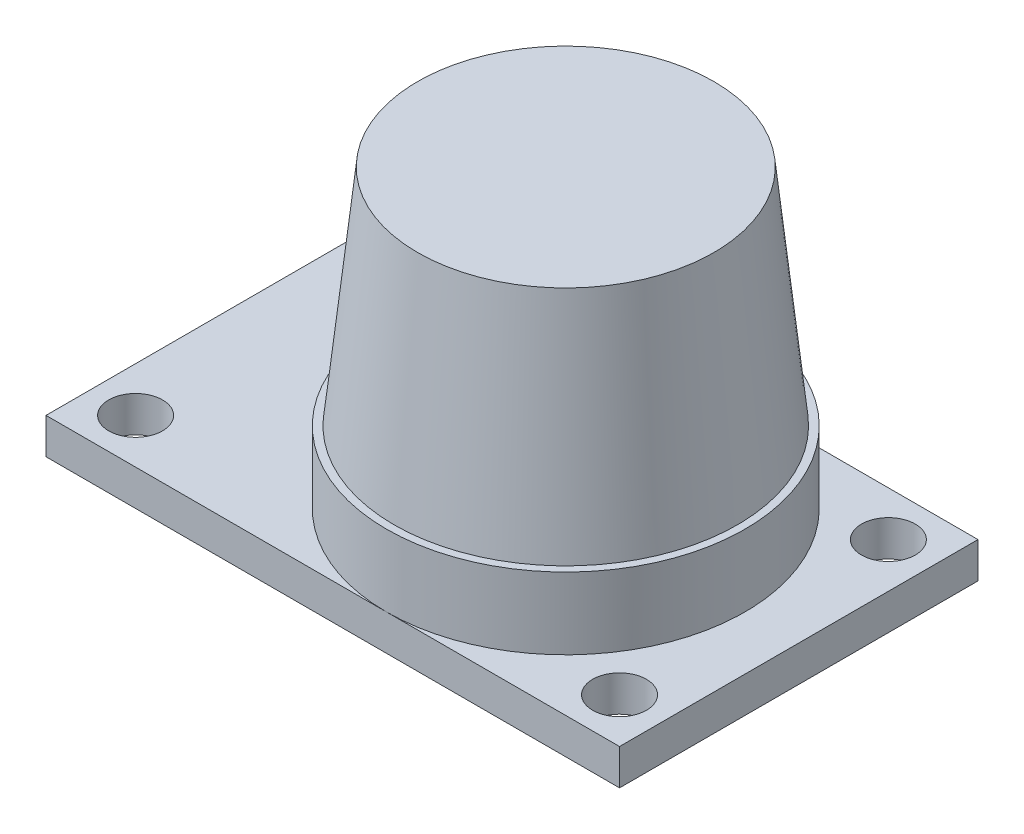
SolidWorks part; units mm, degrees
ref_plane "Alzado" through (0, 0, 0) normal (0, 0, 1) x (1, 0, 0)
ref_plane "Planta" through (0, 0, 0) normal (0, 1, 0) x (1, 0, 0)
ref_plane "Vista lateral" through (0, 0, 0) normal (1, 0, 0) x (0, 0, -1)
sketch "Croquis1" plane through (0, 0, 0) normal (0, 1, 0) x (1, 0, 0)
  line L0 (-13.5, 7.5) -> (-13.5, -7.5) construction
  line L1 (-16, -10) -> (16, -10)
  line L2 (-16, -10) -> (-16, 10)
  line L3 (-16, 10) -> (16, 10)
  line L4 (16, -10) -> (16, 10)
  line L5 (-16, -10) -> (16, 10) construction
  line L6 (-16, 10) -> (16, -10) construction
  line L7 (-13.5, 7.5) -> (13.5, 7.5) construction
  circle A0 centre (-13.5, 7.5) radius 1.5
  circle A1 centre (13.5, 7.5) radius 1.5
  circle A2 centre (-13.5, -7.5) radius 1.5
  circle A3 centre (13.5, -7.5) radius 1.5
  point P0 (0, 0)
  point P8 (-16, 0)
  point P11 (-13.5, 0)
  point P14 (0, 7.5)
  point P17 (0, 10)
  dimension "D5" = 3
  dimension "D1" = 32
  dimension "D2" = 20
  dimension "D3" = 15
  dimension "D4" = 27
extrude "Saliente-Extruir1" add sketch "Croquis1" along normal blind 2
sketch "Croquis2" plane through (0, 2, 0) normal (0, 1, 0) x (1, 0, 0)
  line L0 (16, -10) -> (16, 10) construction
  circle A0 centre (3, 0) radius 10
  dimension "D1" = 20
  dimension "D2" = 13
extrude "Saliente-Extruir2" add sketch "Croquis2" along normal blind 16.5 draft 6
sketch "Croquis4" plane through (0, 2, 0) normal (0, 1, 0) x (1, 0, 0)
  circle A0 centre (3, 0) radius 10 construction
  circle A1 centre (3, 0) radius 10
extrude "Saliente-Extruir3" add sketch "Croquis4" along normal blind 4
